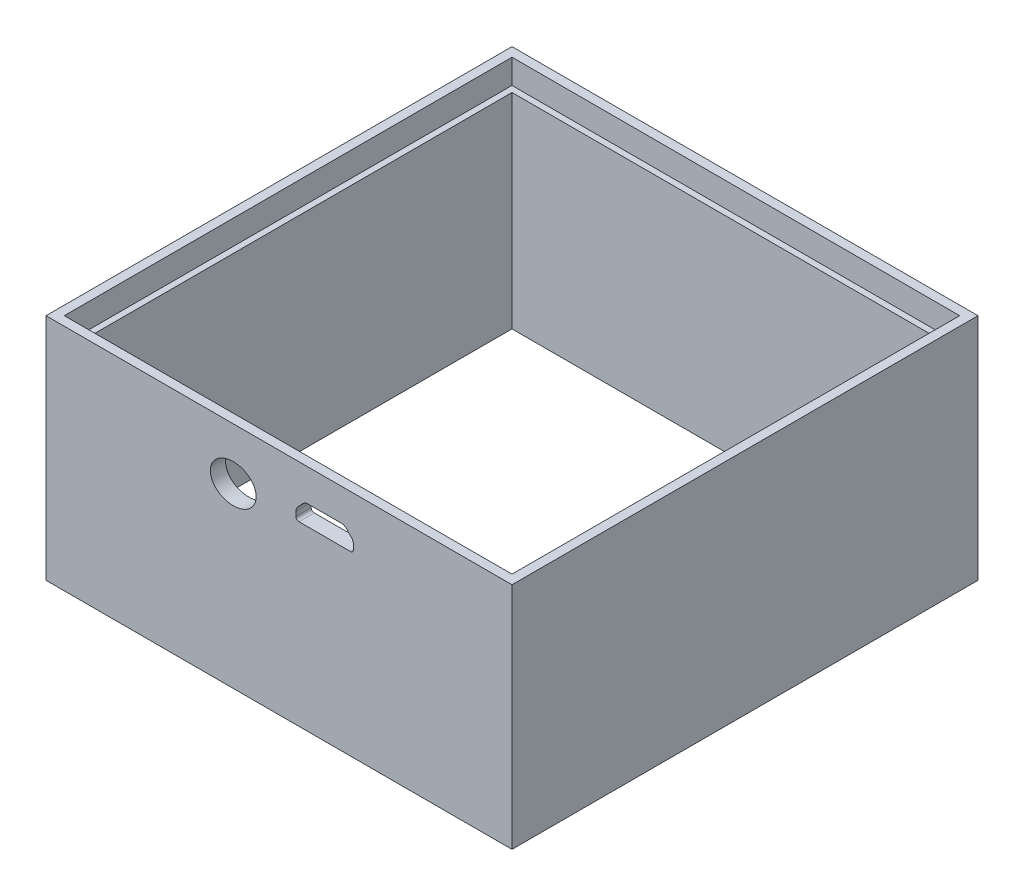
SolidWorks part; units mm, degrees
ref_plane "Front Plane" through (0, 0, 0) normal (0, 0, 1) x (1, 0, 0)
ref_plane "Top Plane" through (0, 0, 0) normal (0, 1, 0) x (1, 0, 0)
ref_plane "Right Plane" through (0, 0, 0) normal (1, 0, 0) x (0, 0, -1)
sketch "Sketch1" plane through (0, 0, 0) normal (0, 1, 0) x (1, 0, 0)
  line L1 (28.5, 0) -> (28.5, 57)
  line L2 (28.5, 57) -> (-28.5, 57)
  line L3 (-28.5, 57) -> (-28.5, 0)
  line L4 (-28.5, 0) -> (28.5, 0)
  line L6 (-30.5, 59) -> (30.5, 59)
  line L7 (30.5, 59) -> (30.5, -2)
  line L8 (30.5, -2) -> (-30.5, -2)
  line L9 (-30.5, -2) -> (-30.5, 59)
extrude "Boss-Extrude2" add sketch "Sketch1" along normal blind 30
sketch "Sketch2" plane through (0, 30, 0) normal (0, 1, 0) x (1, 0, 0)
  line L4 (-29.3, 57.8) -> (-29.3, -0.8)
  line L5 (-29.3, -0.8) -> (29.3, -0.8)
  line L6 (29.3, -0.8) -> (29.3, 57.8)
  line L7 (29.3, 57.8) -> (-29.3, 57.8)
extrude "Cut-Extrude1" cut sketch "Sketch2" against normal blind 3.2
sketch "Sketch4" plane through (0, 0, 0) normal (0, 0, -1) x (-1, 0, 0)
  line L0 (-28.5, 26.8) -> (0, 26.8)
  line L1 (28.5, 26.8) -> (-28.5, 26.8) construction
  line L3 (-5.9828, 25.8) -> (-5.9828, 23.2) construction
  line L4 (-2.6078, 23.2) -> (-9.3578, 23.2)
  line L5 (-9.7578, 23.6) -> (-9.7578, 24.1477)
  line L6 (-9.4792, 24.8402) -> (-8.8529, 25.4925)
  line L7 (-8.1316, 25.8) -> (-3.834, 25.8)
  line L8 (-2.4864, 24.8402) -> (-3.1126, 25.4925)
  line L9 (-2.2078, 23.6) -> (-2.2078, 24.1477)
  arc A0 (-8.8529, 25.4925) -> (-8.1316, 25.8) centre (-8.1316, 24.8) cw
  arc A1 (-3.1126, 25.4925) -> (-3.834, 25.8) centre (-3.834, 24.8) ccw
  arc A2 (-9.7578, 24.1477) -> (-9.4792, 24.8402) centre (-8.7578, 24.1477) cw
  arc A3 (-2.4864, 24.8402) -> (-2.2078, 24.1477) centre (-3.2078, 24.1477) cw
  arc A4 (-9.3578, 23.2) -> (-9.7578, 23.6) centre (-9.3578, 23.6) cw
  arc A5 (-2.2078, 23.6) -> (-2.6078, 23.2) centre (-2.6078, 23.6) cw
  ellipse E0 centre (5.9926, 23.2153) end of major axis (2.9926, 23.2153) minor radius 2.5
  ellipse E1 centre (5.9926, 23.2153) end of major axis (9.4679, 23.2307) minor radius 3
extrude "Cut-Extrude2" cut sketch "Sketch4" against normal through all contours L3 L7 A0 L6 A2 L5 A4 L4 | L7 L3 L4 A5 L9 A3 L8 A1 | E0
